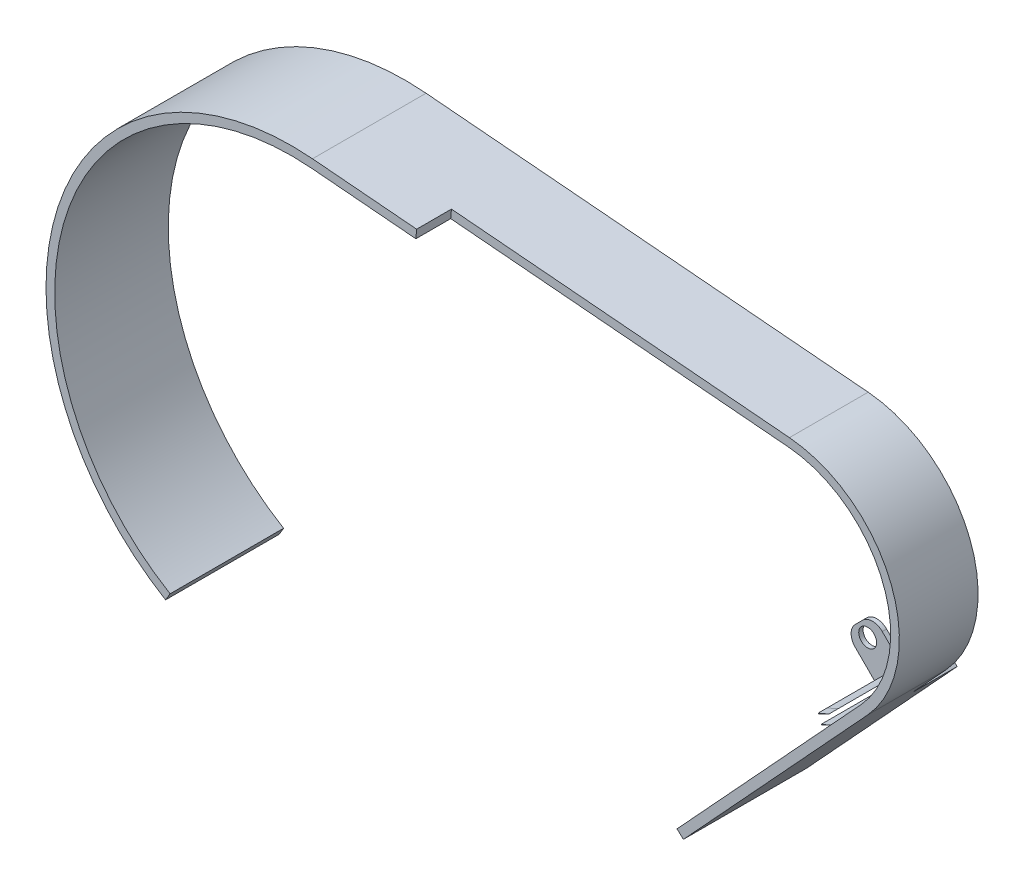
SolidWorks part; units mm, degrees
ref_plane "Front Plane" through (0, 0, 0) normal (0, 0, 1) x (1, 0, 0)
ref_plane "Top Plane" through (0, 0, 0) normal (0, 1, 0) x (1, 0, 0)
ref_plane "Right Plane" through (0, 0, 0) normal (1, 0, 0) x (0, 0, -1)
sketch "Sketch1" plane through (0, 0, 0) normal (0, 0, 1) x (1, 0, 0)
  line L0 (121.6679, 181.2951) -> (282.8673, 167.4918)
  line L1 (153.0564, 18.0749) -> (297.6383, 90.6823)
  line L2 (283.1381, 170.6552) -> (121.9388, 184.4585)
  line L3 (154.4813, 15.2376) -> (298.1618, 87.3924)
  line L4 (36.5877, 50.783) -> (13.6453, 23.6139)
  line L5 (53.8588, 29.1942) -> (22.3162, 12.7753)
  line L6 (68.3731, 18.3914) -> (160.7614, 18.3914) construction
  line L7 (114.3, 95.25) -> (68.3731, 18.3914)
  line L8 (294.8392, 85.7238) -> (264.7021, 85.7238) construction
  line L9 (279.4, 127) -> (294.8392, 85.7238)
  line L10 (309.2815, 99.4554) -> (274.8507, 62.1035)
  line L11 (274.8507, 62.1035) -> (277.1852, 59.9516)
  line L12 (277.1852, 59.9516) -> (311.616, 97.3034)
  circle A1 centre (19.05, 19.05) radius 3.2639 construction
  circle A2 centre (19.05, 19.05) radius 3.2639
  circle A3 centre (19.05, 19.05) radius 7.0739
  arc A4 (25.1637, 15.4915) -> (15.2029, 24.9863) centre (19.05, 19.05) ccw construction
  arc A5 (25.1637, 15.4915) -> (15.2029, 24.9863) centre (19.05, 19.05) ccw
  circle A6 centre (279.4, 127) radius 20.2311 construction
  circle A7 centre (279.4, 127) radius 20.2311
  circle A8 centre (279.4, 127) radius 40.64
  circle A9 centre (114.3, 95.25) radius 35.7643 construction
  circle A10 centre (114.3, 95.25) radius 35.7643
  circle A11 centre (114.3, 95.25) radius 86.36
  circle A12 centre (114.3, 95.25) radius 89.535
  arc A13 (311.616, 97.3034) -> (298.1829, 87.4152) centre (279.4, 127) ccw
  arc A14 (117.9296, 28.7195) -> (118.5852, 20.7913) centre (113.7881, 24.3858) ccw construction
  arc A15 (117.9296, 28.7195) -> (118.5852, 20.7913) centre (113.7881, 24.3858) ccw construction
  arc A16 (261.4121, 86.1246) -> (257.9665, 92.9191) centre (263.5195, 91.4642) ccw construction
  arc A17 (261.4121, 86.1246) -> (257.9665, 92.9191) centre (263.5195, 91.4642) ccw construction
  dimension "D1" = 81.28
  dimension "D2" = 172.72
  dimension "D3" = 3.175
  dimension "D4" = 3.175
  dimension "D5" = 35.56
  dimension "D6" = 35.56
  dimension "D7" = 50.8
extrude "Boss-Extrude1" add sketch "Sketch1" along normal blind 25.4 contours A13 L0 A8 L1 L9 | A8 L9 L1 | A13 L9 L3 | A13 L2 A12 L0 | L0 A12 L7 A11
sketch "Sketch2" plane through (0, 0, 0) normal (0, 0, -1) x (-1, 0, 0)
  line L0 (-114.3, 95.25) -> (-68.3731, 18.3914) construction
  line L1 (-121.6679, 181.2951) -> (-282.8673, 167.4918) construction
  line L2 (-53.8588, 29.1942) -> (-22.3162, 12.7753) construction
  line L3 (-36.5877, 50.783) -> (-13.6453, 23.6139) construction
  line L4 (-154.4813, 15.2376) -> (-298.1618, 87.3924) construction
  line L5 (-283.1381, 170.6552) -> (-121.9388, 184.4585) construction
  line L6 (-153.0564, 18.0749) -> (-297.6383, 90.6823) construction
  line L7 (-279.4, 127) -> (-294.8392, 85.7238) construction
  line L8 (-114.3, 95.25) -> (-68.3731, 18.3914)
  line L9 (-121.6679, 181.2951) -> (-282.8673, 167.4918)
  line L10 (-53.8588, 29.1942) -> (-22.3162, 12.7753)
  line L11 (-36.5877, 50.783) -> (-13.6453, 23.6139)
  line L12 (-154.4813, 15.2376) -> (-298.1618, 87.3924)
  line L13 (-283.1381, 170.6552) -> (-121.9388, 184.4585)
  line L14 (-153.0564, 18.0749) -> (-297.6383, 90.6823)
  line L15 (-279.4, 127) -> (-294.8392, 85.7238)
  arc A0 (-15.2029, 24.9863) -> (-25.1637, 15.4915) centre (-19.05, 19.05) ccw construction
  circle A1 centre (-114.3, 95.25) radius 86.36
  circle A2 centre (-114.3, 95.25) radius 86.36
  circle A3 centre (-114.3, 95.25) radius 35.7643
  circle A4 centre (-114.3, 95.25) radius 35.7643
  circle A5 centre (-279.4, 127) radius 40.64
  circle A6 centre (-279.4, 127) radius 40.64
  circle A7 centre (-279.4, 127) radius 20.2311
  circle A8 centre (-279.4, 127) radius 20.2311
  circle A9 centre (-19.05, 19.05) radius 7.0739
  circle A10 centre (-19.05, 19.05) radius 7.0739
  circle A11 centre (-19.05, 19.05) radius 3.2639
  circle A12 centre (-19.05, 19.05) radius 3.2639
  circle A14 centre (-279.4, 127) radius 43.815
  circle A15 centre (-114.3, 95.25) radius 89.535
  circle A16 centre (-114.3, 95.25) radius 89.535
  arc A17 (-15.2029, 24.9863) -> (-25.1637, 15.4915) centre (-19.05, 19.05) ccw
  arc M16 (-68.3731, 18.3914) -> (-121.9388, 184.4585) centre (-114.3, 95.25) ccw
  dimension "D7" = 87.63
  dimension "D1" = 0
  dimension "D2" = 0
  dimension "D3" = 0
  dimension "D4" = 0
  dimension "D5" = 0
  dimension "D6" = 0
  dimension "D8" = 0
extrude "Boss-Extrude2" add sketch "Sketch2" against normal blind 3.175 contours A10 L11 L10 M16 | A10 A12
sketch "Sketch3" plane through (0, 0, 25.4) normal (0, 0, 1) x (1, 0, 0)
  line L0 (114.3, 95.25) -> (68.3731, 18.3914) construction
  line L1 (121.6679, 181.2951) -> (282.8673, 167.4918) construction
  line L2 (53.8588, 29.1942) -> (22.3162, 12.7753) construction
  line L3 (36.5877, 50.783) -> (13.6453, 23.6139) construction
  line L4 (154.4813, 15.2376) -> (298.1618, 87.3924) construction
  line L5 (283.1381, 170.6552) -> (121.9388, 184.4585) construction
  line L6 (153.0564, 18.0749) -> (297.6383, 90.6823) construction
  line L7 (279.4, 127) -> (294.8392, 85.7238) construction
  line L8 (114.3, 95.25) -> (68.3731, 18.3914)
  line L9 (121.6679, 181.2951) -> (282.8673, 167.4918)
  line L10 (53.8588, 29.1942) -> (22.3162, 12.7753)
  line L11 (36.5877, 50.783) -> (13.6453, 23.6139)
  line L12 (154.4813, 15.2376) -> (298.1618, 87.3924)
  line L13 (283.1381, 170.6552) -> (121.9388, 184.4585)
  line L14 (153.0564, 18.0749) -> (297.6383, 90.6823)
  line L15 (279.4, 127) -> (294.8392, 85.7238)
  arc A0 (25.1637, 15.4915) -> (15.2029, 24.9863) centre (19.05, 19.05) ccw construction
  circle A1 centre (114.3, 95.25) radius 86.36
  circle A2 centre (114.3, 95.25) radius 86.36
  circle A3 centre (114.3, 95.25) radius 35.7643
  circle A4 centre (114.3, 95.25) radius 35.7643
  circle A5 centre (279.4, 127) radius 40.64
  circle A6 centre (279.4, 127) radius 40.64
  circle A7 centre (279.4, 127) radius 20.2311
  circle A8 centre (279.4, 127) radius 20.2311
  circle A9 centre (19.05, 19.05) radius 7.0739
  circle A10 centre (19.05, 19.05) radius 7.0739
  circle A11 centre (19.05, 19.05) radius 3.2639
  circle A12 centre (19.05, 19.05) radius 3.2639
  circle A14 centre (279.4, 127) radius 43.815
  circle A15 centre (114.3, 95.25) radius 89.535
  circle A16 centre (114.3, 95.25) radius 89.535
  arc A17 (25.1637, 15.4915) -> (15.2029, 24.9863) centre (19.05, 19.05) ccw
  arc M9 (311.616, 97.3034) -> (283.1381, 170.6552) centre (279.4, 127) ccw
  line M10 (283.1381, 170.6552) -> (121.9388, 184.4585)
  arc M11 (121.9388, 184.4585) -> (68.3731, 18.3914) centre (114.3, 95.25) ccw
  line M12 (68.3731, 18.3914) -> (70.0017, 21.1169)
  arc M13 (70.0017, 21.1169) -> (121.6679, 181.2951) centre (114.3, 95.25) cw
  line M14 (121.6679, 181.2951) -> (282.8673, 167.4918)
  arc M15 (282.8673, 167.4918) -> (309.2815, 99.4554) centre (279.4, 127) cw
  line M16 (294.7502, 85.9619) -> (294.8392, 85.7238)
  line M17 (294.8392, 85.7238) -> (298.1618, 87.3924)
  dimension "D7" = 87.63
  dimension "D1" = 0
  dimension "D2" = 0
  dimension "D3" = 0
  dimension "D4" = 0
  dimension "D5" = 0
  dimension "D6" = 0
  dimension "D8" = 0
extrude "Boss-Extrude3" add sketch "Sketch3" along normal blind 3.302 contours A16 M14 M11 M12 M13 | A16 L9 A14 M10 | A14 L9 L14 M9 M15 M16 | L14 M16 M15 | A14 L15 M17 | A2
sketch "Sketch4" plane through (0, 0, 28.702) normal (0, 0, 1) x (1, 0, 0)
  line L0 (121.6679, 181.2951) -> (282.8673, 167.4918) construction
  line L1 (283.1381, 170.6552) -> (121.9388, 184.4585) construction
  line L2 (121.6679, 181.2951) -> (159.629, 178.0446)
  line L3 (159.8999, 181.208) -> (121.9388, 184.4585)
  line L4 (159.8999, 181.208) -> (159.629, 178.0446)
  line L5 (121.9388, 184.4585) -> (121.6679, 181.2951) construction
  line L6 (68.3731, 18.3914) -> (70.0017, 21.1169) construction
  line L7 (68.3731, 18.3914) -> (70.0017, 21.1169)
  arc A0 (121.6679, 181.2951) -> (70.0017, 21.1169) centre (114.3, 95.25) ccw construction
  arc A1 (121.9388, 184.4585) -> (68.3731, 18.3914) centre (114.3, 95.25) ccw construction
  arc A2 (121.6679, 181.2951) -> (70.0017, 21.1169) centre (114.3, 95.25) ccw
  arc A3 (121.9388, 184.4585) -> (68.3731, 18.3914) centre (114.3, 95.25) ccw
  dimension "D1" = 38.1
extrude "Boss-Extrude4" add sketch "Sketch4" along normal blind 12.7
sketch "Sketch5" plane through (0, 0, 0) normal (0, 0, -1) x (-1, 0, 0)
  line L0 (-277.1852, 59.9516) -> (-274.8507, 62.1035)
  line L1 (-274.8507, 62.1035) -> (-297.0701, 86.208)
  line L2 (-297.0701, 86.208) -> (-299.4046, 84.0561)
  line L3 (-277.1852, 59.9516) -> (-311.616, 97.3034) construction
  line L4 (-299.4046, 84.0561) -> (-277.1852, 59.9516)
extrude "Boss-Extrude5" add sketch "Sketch5" along normal blind 16.1925
sketch "Sketch6" plane through (0, 0, -16.1925) normal (0, 0, -1) x (-1, 0, 0)
  line L0 (-274.8507, 62.1035) -> (-263.8012, 73.153)
  line L1 (-263.8012, 80.3372) -> (-266.4953, 83.0312)
  line L2 (-273.6795, 83.0312) -> (-284.327, 72.3838)
  line L3 (-274.8507, 62.1035) -> (-297.0701, 86.208) construction
  line L4 (-284.327, 72.3838) -> (-274.8507, 62.1035)
  line L5 (-265.1483, 81.6842) -> (-279.5888, 67.2436) construction
  line L6 (-272.3685, 74.4639) -> (-267.4294, 69.5248) construction
  line L7 (-272.3685, 74.4639) -> (-277.3077, 79.4031) construction
  circle A0 centre (-268.3542, 78.4783) radius 3.2639
  arc A1 (-266.4953, 83.0312) -> (-273.6795, 83.0312) centre (-270.0874, 79.4391) ccw
  arc A2 (-263.8012, 73.153) -> (-263.8012, 80.3372) centre (-267.3933, 76.7451) ccw
  dimension "D2" = 6.5278
  dimension "D3" = 4.5339
  dimension "D5" = 5.08
  dimension "D1" = 13.97
  dimension "D4" = 15.875
extrude "Boss-Extrude6" add sketch "Sketch6" against normal blind 1.5875
sketch "Sketch7" plane through (0, 0, -16.1925) normal (0, 0, -1) x (-1, 0, 0)
  line L0 (-277.1852, 59.9516) -> (-244.4759, 24.4674)
  line L1 (-244.4759, 24.4674) -> (-242.1414, 26.6193)
  line L2 (-242.1414, 26.6193) -> (-274.8507, 62.1035)
  line L3 (-284.327, 72.3838) -> (-297.0701, 86.208) construction
  line L4 (-299.4046, 84.0561) -> (-277.1852, 59.9516) construction
  line L5 (-277.1852, 59.9516) -> (-274.8507, 62.1035) construction
  line L13 (-299.4046, 84.0561) -> (-277.1852, 59.9516)
  line L14 (-277.1852, 59.9516) -> (-274.8507, 62.1035)
  line L15 (-274.8507, 62.1035) -> (-263.8012, 73.153)
  line L16 (-263.8012, 80.3372) -> (-266.4953, 83.0312)
  line L17 (-273.6795, 83.0312) -> (-284.327, 72.3838)
  line L18 (-284.327, 72.3838) -> (-297.0701, 86.208)
  line L19 (-297.0701, 86.208) -> (-299.4046, 84.0561)
  line L21 (-277.1852, 59.9516) -> (-274.8507, 62.1035)
  arc A2 (-263.8012, 73.153) -> (-263.8012, 80.3372) centre (-267.3933, 76.7451) ccw
  arc A3 (-266.4953, 83.0312) -> (-273.6795, 83.0312) centre (-270.0874, 79.4391) ccw
  dimension "D1" = 48.26
  dimension "D2" = 0
extrude "Boss-Extrude7" add sketch "Sketch7" against normal up to surface (44.8945 mm away) up to face at (295.0067, 89.4263, 28.702)
